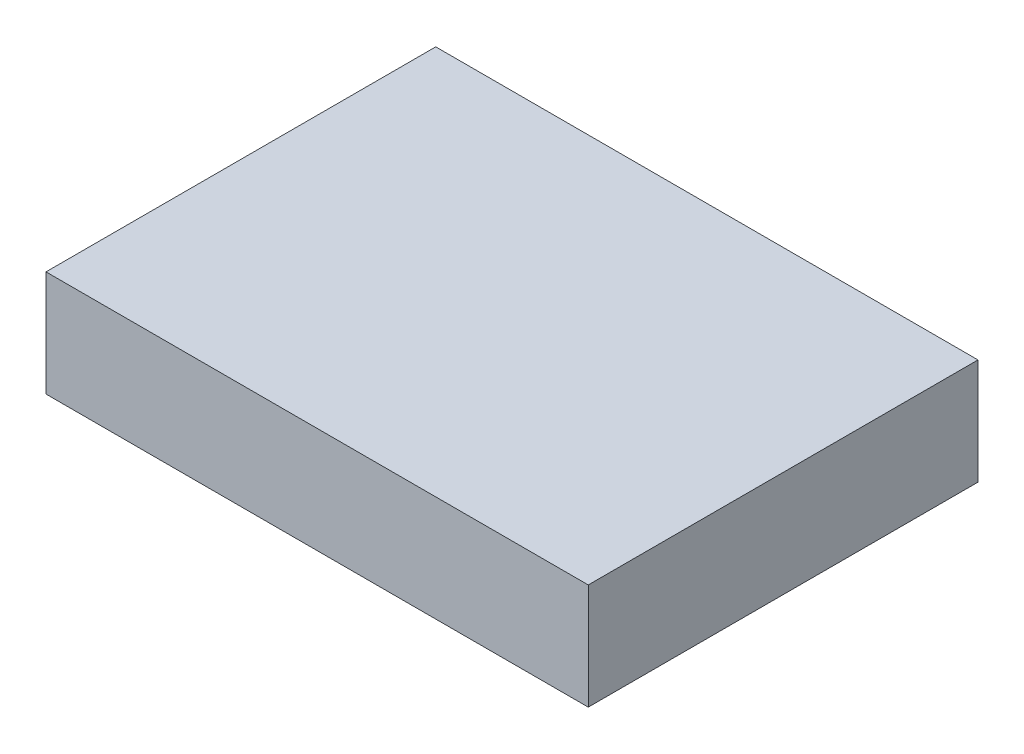
SolidWorks part; units mm, degrees
ref_plane "前视基准面" through (0, 0, 0) normal (0, 0, 1) x (1, 0, 0)
ref_plane "上视基准面" through (0, 0, 0) normal (0, 1, 0) x (1, 0, 0)
ref_plane "右视基准面" through (0, 0, 0) normal (1, 0, 0) x (0, 0, -1)
sketch "草图1" plane through (0, 0, 0) normal (0, 1, 0) x (1, 0, 0)
  line L1 (-56.35, -40.5) -> (56.35, -40.5)
  line L2 (-56.35, -40.5) -> (-56.35, 40.5)
  line L3 (-56.35, 40.5) -> (56.35, 40.5)
  line L4 (56.35, -40.5) -> (56.35, 40.5)
  line L5 (-56.35, -40.5) -> (56.35, 40.5) construction
  line L6 (-56.35, 40.5) -> (56.35, -40.5) construction
  point P0 (0, 0)
  dimension "D1" = 112.7
  dimension "D2" = 81
extrude "凸台-拉伸1" add sketch "草图1" along normal blind 22
